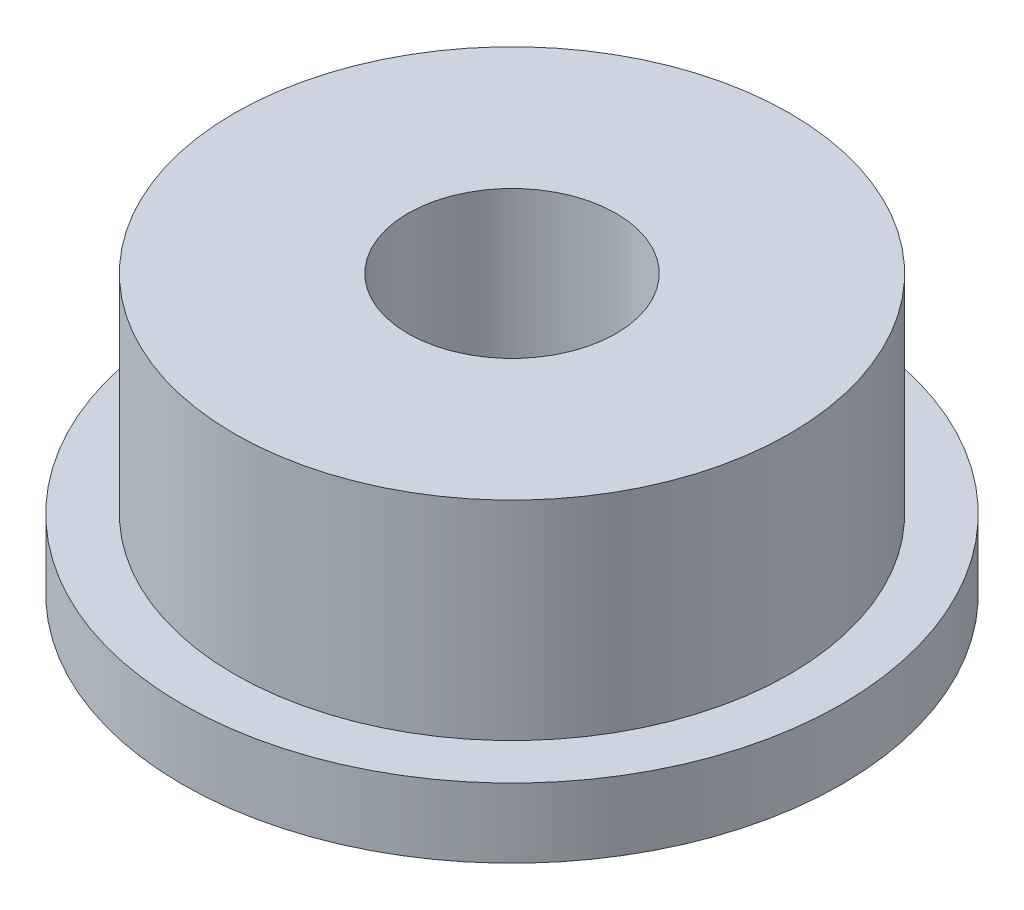
SolidWorks part; units mm, degrees
material "201 退火不锈钢 (SS)"
ref_plane "前视基准面" through (0, 0, 0) normal (0, 0, 1) x (1, 0, 0)
ref_plane "上视基准面" through (0, 0, 0) normal (0, 1, 0) x (1, 0, 0)
ref_plane "右视基准面" through (0, 0, 0) normal (1, 0, 0) x (0, 0, -1)
sketch "草图1" plane through (0, 0, 0) normal (0, 1, 0) x (1, 0, 0)
  circle A0 centre (0, 0) radius 1.5
  circle A1 centre (0, 0) radius 4.75
  dimension "D1" = 3
  dimension "D2" = 9.5
extrude "凸台-拉伸1" add sketch "草图1" along normal blind 1
sketch "草图2" plane through (0, 1, 0) normal (0, 1, 0) x (1, 0, 0)
  circle A0 centre (0, 0) radius 1.5 construction
  circle A1 centre (0, 0) radius 1.5
  circle A2 centre (0, 0) radius 4
  dimension "D1" = 8
extrude "凸台-拉伸2" add sketch "草图2" along normal blind 3
